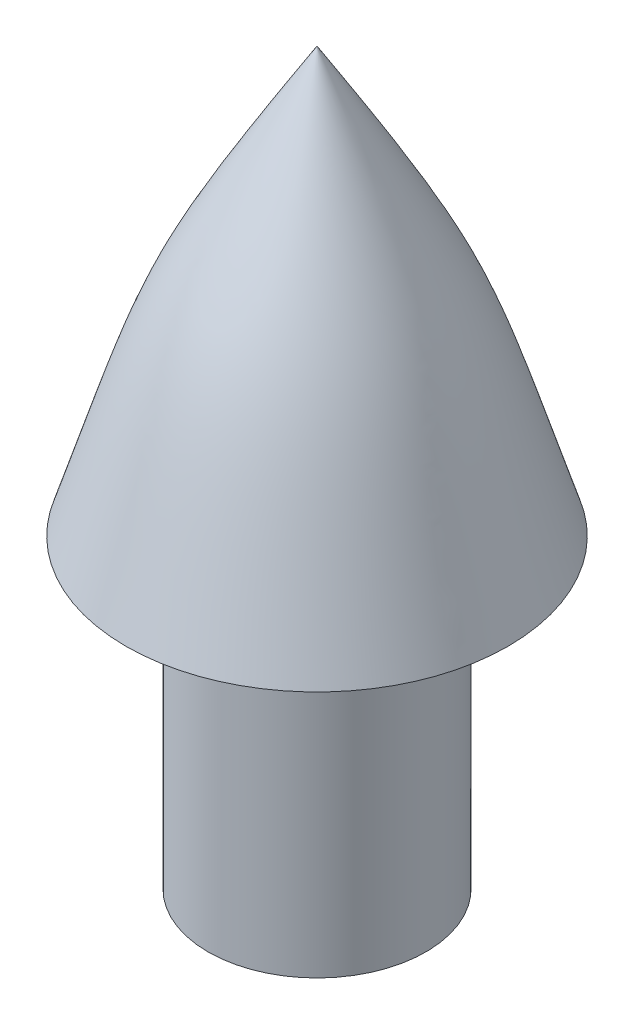
SolidWorks part; units mm, degrees
ref_plane "Front Plane" through (0, 0, 0) normal (0, 0, 1) x (1, 0, 0)
ref_plane "Top Plane" through (0, 0, 0) normal (0, 1, 0) x (1, 0, 0)
ref_plane "Right Plane" through (0, 0, 0) normal (1, 0, 0) x (0, 0, -1)
sketch "Sketch1" plane through (0, 0, 0) normal (0, 0, 1) x (1, 0, 0)
  line L0 (0, 5.8587) -> (0, -5.6917) construction
  line L1 (2.5, 0) -> (1.425, 0)
  line L2 (1.425, 0) -> (1.425, -4)
  line L3 (1.425, -4) -> (0, -4)
  line L4 (0, -4) -> (0, 5.55)
  spline S0 degree 3 poles (0, 5.55) (1.7448, 2.7146) (1.6375, 2.7407) (2.5, 0) knots 0 0 0 0 1 1 1 1
  point P9 (2.6383, 0.1065)
  dimension "D1" = 2.5
  dimension "D2" = 1.425
  dimension "D3" = 5.55
  dimension "D4" = 4
revolve "Revolve1" add sketch "Sketch1" angle 360 about L0
